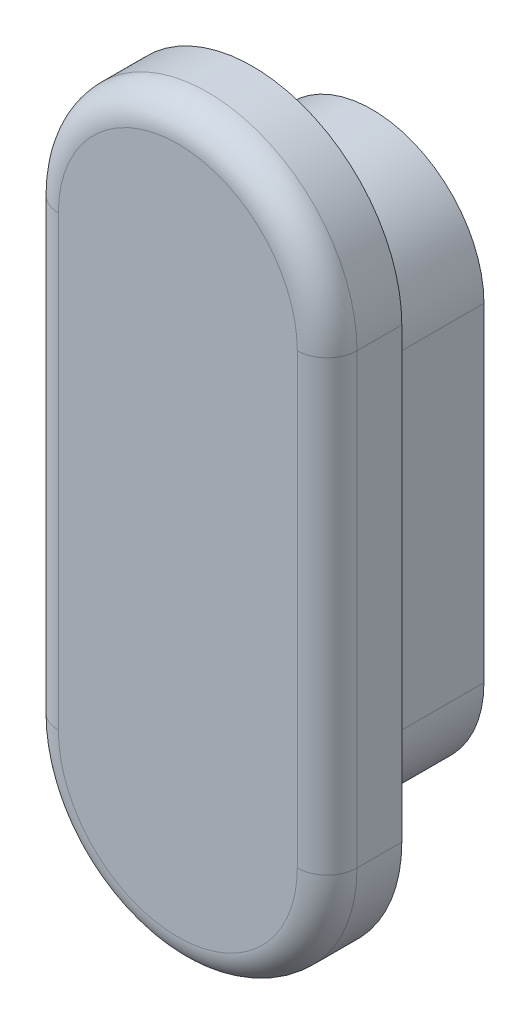
SolidWorks part; units mm, degrees
ref_plane "前视基准面" through (0, 0, 0) normal (0, 0, 1) x (1, 0, 0)
ref_plane "上视基准面" through (0, 0, 0) normal (0, 1, 0) x (1, 0, 0)
ref_plane "右视基准面" through (0, 0, 0) normal (1, 0, 0) x (0, 0, -1)
other "Configuration Table"
sketch "草图2" plane through (0, 0, 0) normal (0, 0, 1) x (1, 0, 0)
  line L0 (0, -11) -> (0, 11) construction
  line L1 (-7.5, -11) -> (-7.5, 11)
  line L2 (7.5, -11) -> (7.5, 11)
  arc A0 (-7.5, -11) -> (7.5, -11) centre (0, -11) ccw
  arc A1 (7.5, 11) -> (-7.5, 11) centre (0, 11) ccw
  circle A2 centre (0, -11) radius 2
  circle A3 centre (0, 11) radius 2
  point P2 (0, 0)
  point P12 (0, 0)
  point P13 (0, 0)
  point P14 (0, 0)
  point P15 (0, 0)
  dimension "D1" = 22
  dimension "D2" = 15
extrude "凸台-拉伸1" add sketch "草图2" along normal blind 8
sketch "草图3" plane through (0, 0, 8) normal (0, 0, 1) x (1, 0, 0)
  line L0 (0, -15) -> (0, 15) construction
  line L1 (-10, -15) -> (-10, 15)
  line L2 (10, -15) -> (10, 15)
  arc A0 (-10, -15) -> (10, -15) centre (0, -15) ccw
  arc A1 (10, 15) -> (-10, 15) centre (0, 15) ccw
  point P2 (0, 0)
  dimension "D1" = 20
  dimension "D2" = 15
extrude "凸台-拉伸2" add sketch "草图3" along normal blind 5
fillet "圆角1" radius 2 4 edges at (10, 0, 13) (0, -25, 13) (-10, 0, 13) (0, 25, 13)
